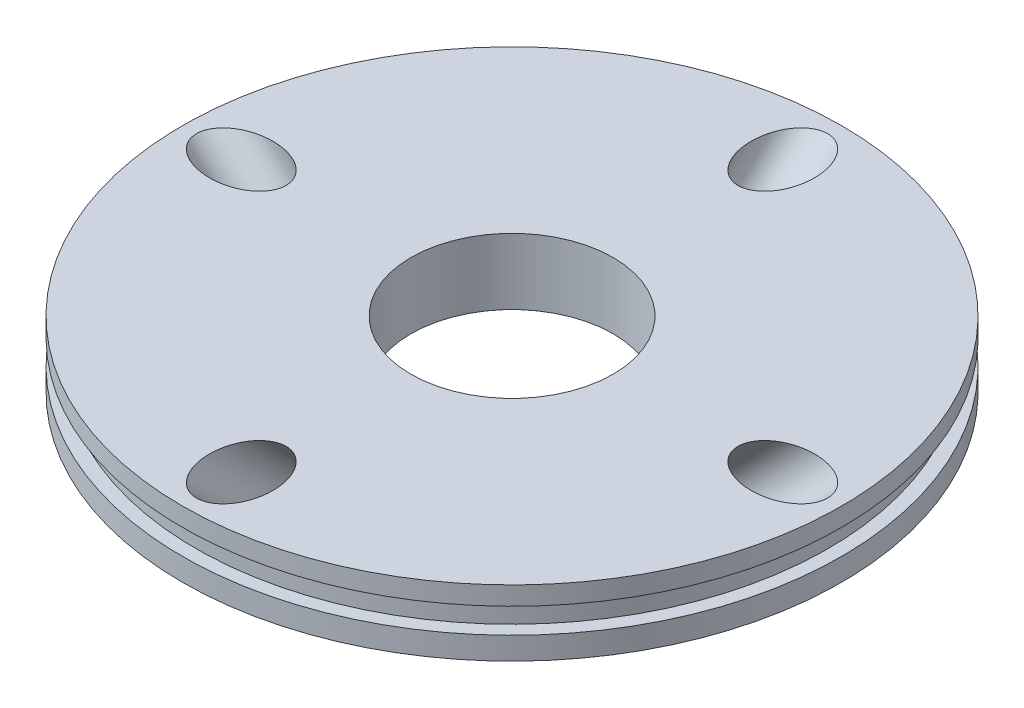
SolidWorks part; units mm, degrees
material "AISI 304"
ref_plane "Front Plane" through (0, 0, 0) normal (0, 0, 1) x (1, 0, 0)
ref_plane "Top Plane" through (0, 0, 0) normal (0, 1, 0) x (1, 0, 0)
ref_plane "Right Plane" through (0, 0, 0) normal (1, 0, 0) x (0, 0, -1)
sketch "Sketch1" plane through (0, 0, 0) normal (0, 1, 0) x (1, 0, 0)
  circle A1 centre (0, 0) radius 31.6865
  dimension "D2" = 63.373
extrude "Boss-Extrude1" add sketch "Sketch1" along normal blind 6.35
ref_plane "Plane1" through (0, 3.175, 0) normal (0, 1, 0) x (1, 0, 0)
sketch "Sketch4" plane through (0, 0, 0) normal (0, 0, 1) x (1, 0, 0)
  line L0 (-28.4727, 8.7877) -> (-22.86, 3.175)
  line L4 (31.4325, 3.175) -> (-31.4325, 3.175) construction
  line L5 (-22.86, 3.175) -> (-17.2473, -2.4377)
  line L6 (0, -3.4925) -> (0, 3.4925) construction
  line L7 (-28.4727, 8.7877) -> (-26.3174, 10.9429)
  line L8 (-26.3174, 10.9429) -> (-15.0921, -0.2824)
  line L9 (-15.0921, -0.2824) -> (-17.2473, -2.4377)
  dimension "D1" = 22.86
  dimension "D2" = 3.048
  dimension "D3" = 15.875
  dimension "D4" = 45
revolve "Cut-Revolve1" cut sketch "Sketch4" angle 360 about L0
ref_axis "Axis2" through (0, -0.3175, 0) along (0, 1, 0)
pattern_circular "CirPattern1" count 4 over 360 about axis through (0, -0.3175, 0) along (0, 1, 0) of "Cut-Revolve1"
sketch "Sketch5" plane through (0, 0, 0) normal (0, 0, 1) x (1, 0, 0)
  line L0 (31.6865, 0) -> (31.6865, 6.35) construction
  line L1 (30.3911, 2.159) -> (31.6865, 2.159)
  line L2 (30.3911, 2.159) -> (30.3911, 4.572)
  line L3 (30.3911, 4.572) -> (31.6865, 4.572)
  line L4 (31.6865, 2.159) -> (31.6865, 4.572)
  line L5 (31.6865, 6.35) -> (-31.6865, 6.35) construction
  line L7 (0, -0.3175) -> (0, 6.6675) construction
  dimension "D1" = 30.3911
  dimension "D2" = 2.413
  dimension "D3" = 1.778
  dimension "D4" = 1.2954
revolve "Cut-Revolve2" cut sketch "Sketch5" angle 360 about axis through (0, -0.3175, 0) along (0, 1, 0)
hole_wizard "3/4 Clearance Hole1" positions "Sketch7" profile "Sketch6" hole size "3/4" standard "ANSI Inch"
sketch "Sketch7" plane through (0, 6.35, 0) normal (0, 1, 0) x (1, 0, 0)
  point P0 (0, 0)
sketch "Sketch6" plane through (0, 6.35, 0) normal (1, 0, 0) x (0, 0, 1)
  line L0 (0, 0) -> (0, 12.1922)
  line L1 (0, 12.1922) -> (9.7231, 6.35)
  line L2 (9.7231, 6.35) -> (9.7231, 0)
  line L5 (9.7231, 0) -> (0, 0)
  line L10 (0, 12.1922) -> (-9.7231, 6.35) construction
  line L11 (0, -6.35) -> (0, 107.95) construction
  dimension "Hole Dia." = 19.4462
  dimension "Hole Depth" = 6.35
  dimension "Drill Angle" = 118
equation "\"D3@Sketch5\"=.07"
